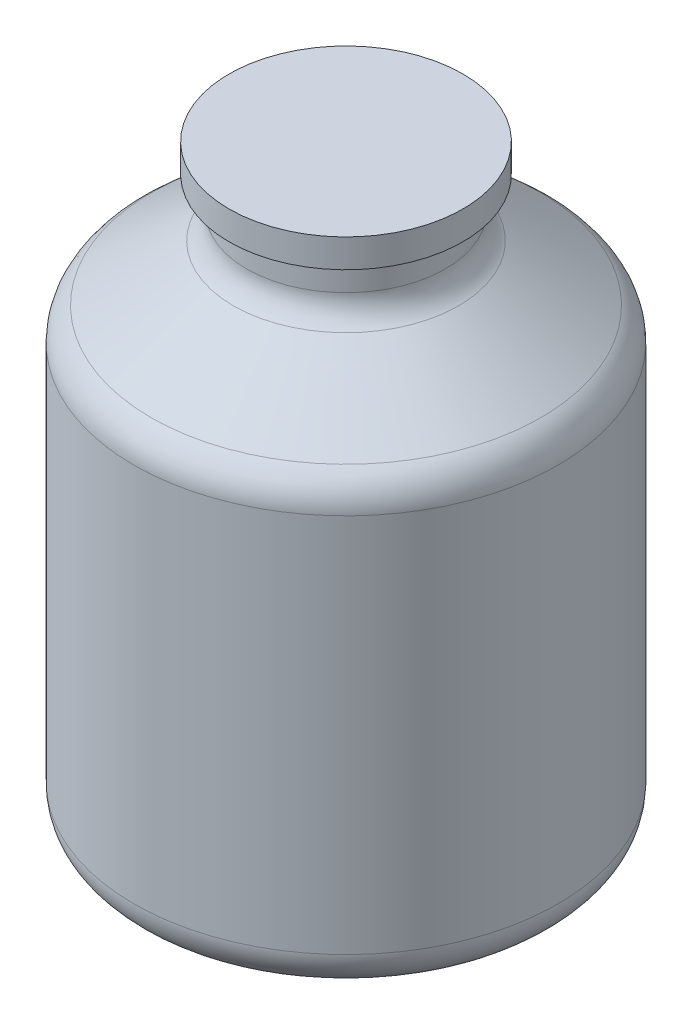
SolidWorks part; units mm, degrees
ref_plane "Front Plane" through (0, 0, 0) normal (0, 0, 1) x (1, 0, 0)
ref_plane "Top Plane" through (0, 0, 0) normal (0, 1, 0) x (1, 0, 0)
ref_plane "Right Plane" through (0, 0, 0) normal (1, 0, 0) x (0, 0, -1)
sketch "Sketch1" plane through (0, 0, 0) normal (0, 0, 1) x (1, 0, 0)
  line L0 (0, 0) -> (55.8506, 0)
  line L1 (68.5506, 12.7) -> (68.5506, 135.5371)
  line L2 (62.9889, 146.0411) -> (36.4262, 164.0924)
  line L3 (32.1096, 172.2449) -> (32.1096, 182.693)
  line L4 (32.1096, 182.693) -> (37.8125, 182.693)
  line L5 (37.8125, 182.693) -> (37.8125, 191.89)
  line L6 (37.8125, 191.89) -> (0, 191.89)
  line L7 (0, 191.89) -> (0, 0)
  arc A0 (55.8506, 0) -> (68.5506, 12.7) centre (55.8506, 12.7) ccw
  arc A1 (68.5506, 135.5371) -> (62.9889, 146.0411) centre (55.8506, 135.5371) ccw
  arc A2 (36.4262, 164.0924) -> (32.1096, 172.2449) centre (41.9665, 172.2449) cw
  dimension "D1" = 12.7
revolve "Revolve1" add sketch "Sketch1" angle 360 about L7
